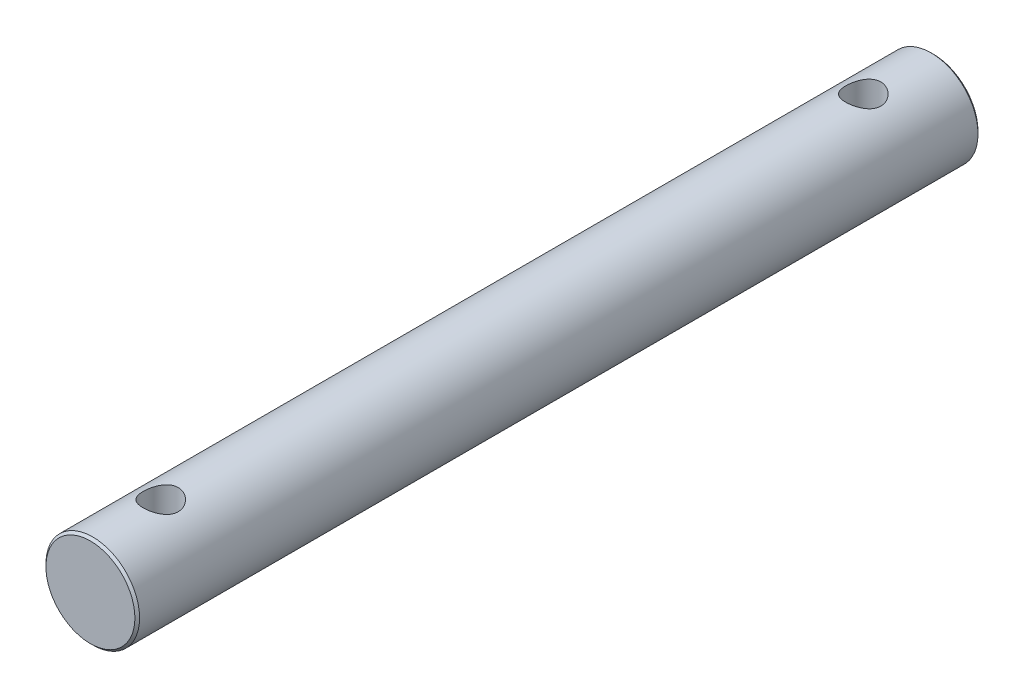
SolidWorks part; units mm, degrees
material "炭素鋼(普通)"
ref_plane "正面" through (0, 0, 0) normal (0, 0, 1) x (1, 0, 0)
ref_plane "平面" through (0, 0, 0) normal (0, 1, 0) x (1, 0, 0)
ref_plane "右側面" through (0, 0, 0) normal (1, 0, 0) x (0, 0, -1)
sketch "ｽｹｯﾁ1" plane through (0, 0, 0) normal (0, 0, 1) x (1, 0, 0)
  circle A0 centre (0, 0) radius 4
  dimension "D1" = 8
extrude "ﾎﾞｽ - 押し出し1" add sketch "ｽｹｯﾁ1" along normal mid plane 52
sketch "ｽｹｯﾁ2" plane through (0, 0, 0) normal (0, 0, 1) x (1, 0, 0)
  circle A0 centre (0, 0) radius 4
  dimension "D1" = 8
extrude "ﾎﾞｽ - 押し出し2" add sketch "ｽｹｯﾁ2" along normal mid plane 72
sketch "ｽｹｯﾁ3" plane through (0, 0, 0) normal (0, 1, 0) x (1, 0, 0)
  line L0 (0, 55.1116) -> (0, -55.1116) construction
  line L1 (4, 36) -> (-4, 36) construction
  circle A0 centre (0, 30) radius 1.5
  dimension "D1" = 3
  dimension "D2" = 6
extrude "ｶｯﾄ - 押し出し1" cut sketch "ｽｹｯﾁ3" against normal through all both and the other way through all
mirror "ﾐﾗｰ1" about plane through (0, 0, 0) normal (0, 0, 1) of "ｶｯﾄ - 押し出し1"
chamfer "面取り1" distance 0.2 angle 45 2 edges at (4, 0, -36) (4, 0, 36)
